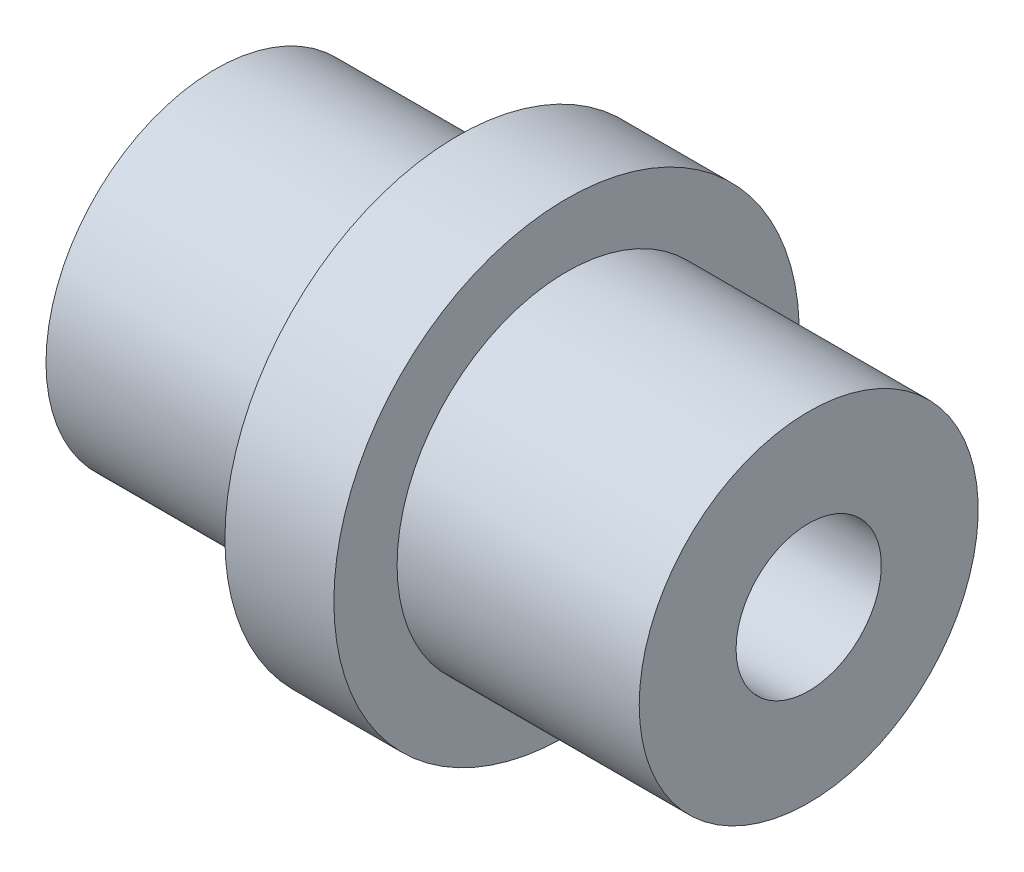
SolidWorks part; units mm, degrees
material "Acciaio inossidabile fuso"
ref_plane "Piano frontale" through (0, 0, 0) normal (0, 0, 1) x (1, 0, 0)
ref_plane "Piano superiore" through (0, 0, 0) normal (0, 1, 0) x (1, 0, 0)
ref_plane "Piano destro" through (0, 0, 0) normal (1, 0, 0) x (0, 0, -1)
sketch "Schizzo1" plane through (0, 0, 0) normal (0, 0, 1) x (1, 0, 0)
  line L0 (0, 3) -> (0, 7)
  line L1 (0, 7) -> (10, 7)
  line L2 (10, 7) -> (10, 9.611)
  line L3 (10, 9.611) -> (14.5, 9.611)
  line L4 (14.5, 9.611) -> (14.5, 7)
  line L5 (14.5, 7) -> (24.5, 7)
  line L6 (24.5, 7) -> (24.5, 3)
  line L7 (24.5, 3) -> (0, 3)
  line L8 (0, 0) -> (18.4828, 0) construction
  dimension "D1" = 6
  dimension "D2" = 14
  dimension "D3" = 24.5
  dimension "D4" = 10
revolve "Rivoluzione1" add sketch "Schizzo1" angle 360 about L8
